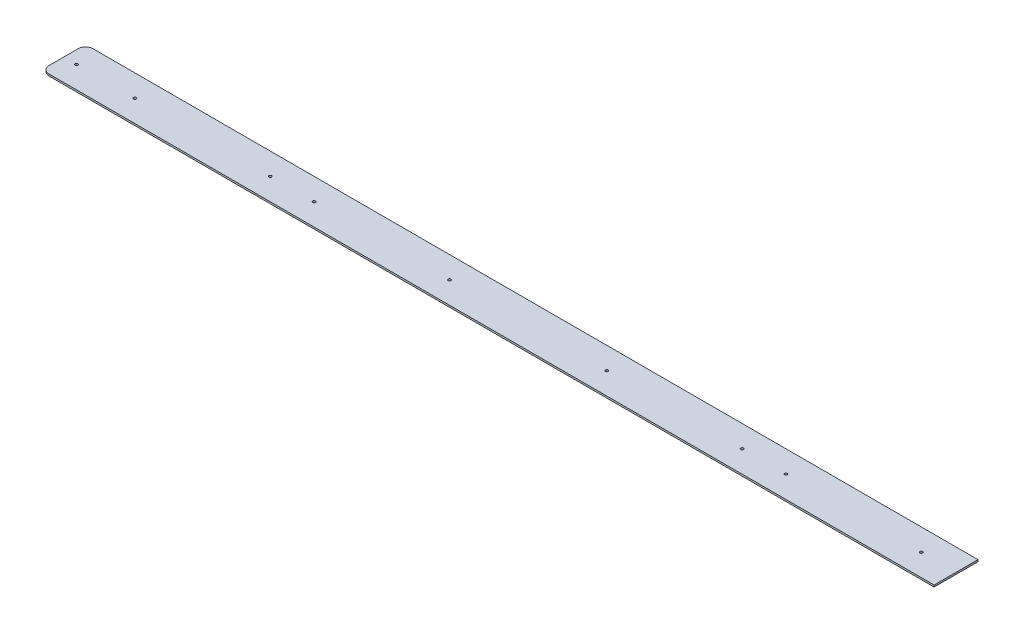
SolidWorks part; units mm, degrees
ref_plane "front" through (0, 0, 0) normal (0, 0, 1) x (1, 0, 0)
ref_plane "top" through (0, 0, 0) normal (0, 1, 0) x (1, 0, 0)
ref_plane "right" through (0, 0, 0) normal (1, 0, 0) x (0, 0, -1)
sketch "Sketch1" plane through (0, 0, 0) normal (0, 1, 0) x (-1, 0, 0)
  line L0 (0, 38.1) -> (0, -38.1)
  line L1 (0, -38.1) -> (1536.7, -38.1)
  line L2 (1549.4, -25.4) -> (1549.4, 25.4)
  line L3 (1536.7, 38.1) -> (0, 38.1)
  circle A0 centre (60.325, 0) radius 2.3876
  circle A1 centre (295.275, 0) radius 2.3876
  circle A2 centre (371.475, 0) radius 2.3876
  circle A3 centre (606.425, 0) radius 2.3876
  circle A4 centre (879.475, 0) radius 2.3876
  circle A5 centre (1114.425, 0) radius 2.3876
  circle A6 centre (1190.625, 0) radius 2.3876
  circle A7 centre (1425.575, 0) radius 2.3876
  circle A8 centre (1527.175, 0) radius 2.3876
  arc A12 (1536.7, -38.1) -> (1549.4, -25.4) centre (1536.7, -25.4) ccw
  arc A13 (1549.4, 25.4) -> (1536.7, 38.1) centre (1536.7, 25.4) ccw
  dimension "D3" = 4.7752
  dimension "D16" = 12.7
  dimension "D1" = 76.2
  dimension "D2" = 1549.4
  dimension "D4" = 60.325
  dimension "D6" = 76.2
  dimension "D9" = 101.6
  dimension "D12" = 76.2
  dimension "D14" = 273.05
extrude "Extrude1" add sketch "Sketch1" against normal blind 3.175
